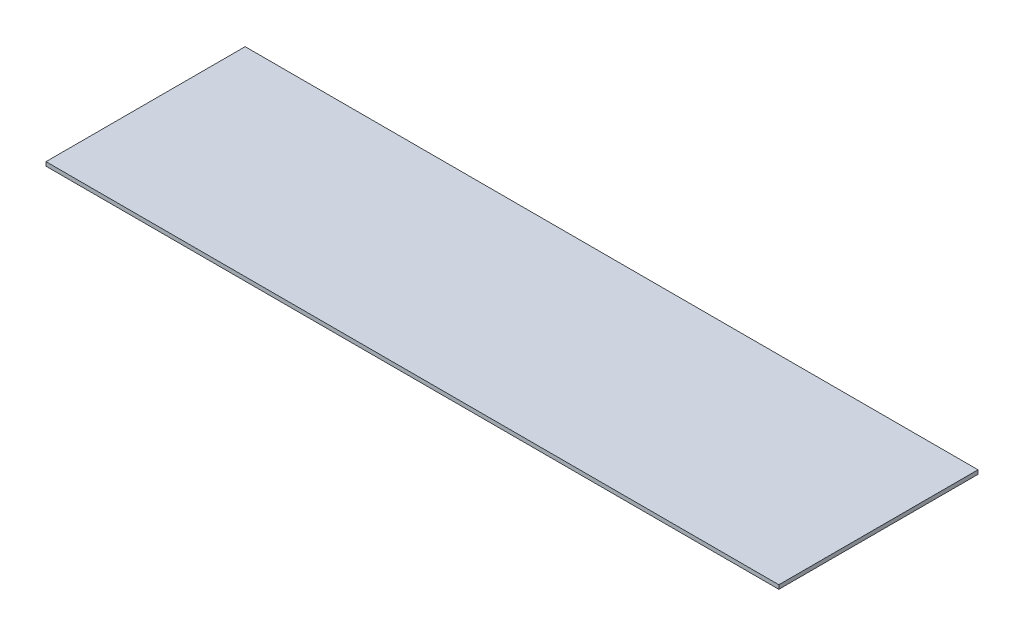
SolidWorks part; units mm, degrees
ref_plane "Front Plane" through (0, 0, 0) normal (0, 0, 1) x (1, 0, 0)
ref_plane "Top Plane" through (0, 0, 0) normal (0, 1, 0) x (1, 0, 0)
ref_plane "Right Plane" through (0, 0, 0) normal (1, 0, 0) x (0, 0, -1)
sketch "Sketch1" plane through (0, 0, 0) normal (0, 1, 0) x (1, 0, 0)
  line L1 (-460, -125) -> (460, -125)
  line L2 (-460, -125) -> (-460, 125)
  line L3 (-460, 125) -> (460, 125)
  line L4 (460, -125) -> (460, 125)
  line L5 (0, 125) -> (0, -125) construction
  line L6 (-460, 0) -> (460, 0) construction
  point P0 (0, 0)
  dimension "D1" = 920
  dimension "D2" = 250
extrude "Boss-Extrude1" add sketch "Sketch1" along normal blind 5
